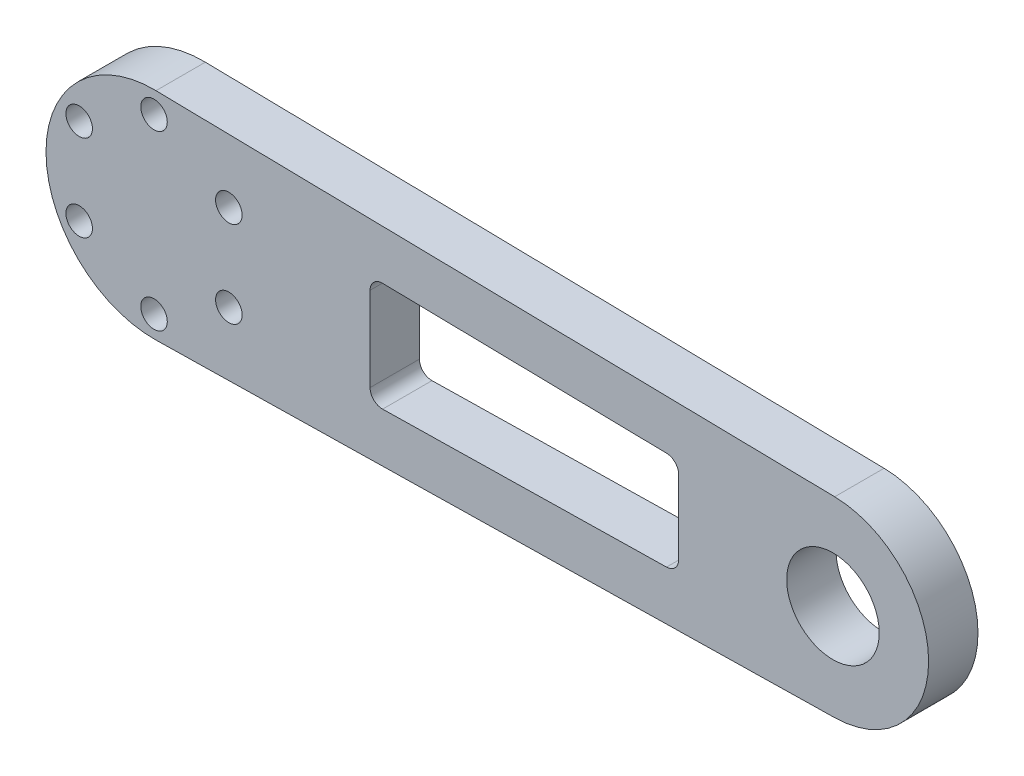
SolidWorks part; units mm, degrees
ref_plane "Front Plane" through (0, 0, 0) normal (0, 0, 1) x (1, 0, 0)
ref_plane "Top Plane" through (0, 0, 0) normal (0, 1, 0) x (1, 0, 0)
ref_plane "Right Plane" through (0, 0, 0) normal (1, 0, 0) x (0, 0, -1)
sketch "Sketch1" plane through (0, 0, 0) normal (0, 0, 1) x (1, 0, 0)
  line L0 (0, 0) -> (110, 0) construction
  line L1 (0.3182, 17.4971) -> (110.2818, 15.4974)
  line L2 (110, 0) -> (125.5, 0) construction
  line L3 (0.3182, -17.4971) -> (110.2818, -15.4974)
  line L4 (35, 6.8284) -> (35, -6.8284)
  line L5 (37.0364, 8.8281) -> (83.0364, 7.9916)
  line L6 (85, 5.9919) -> (85, -5.9919)
  line L7 (37.0364, -8.8281) -> (83.0364, -7.9916)
  circle A0 centre (0, 0) radius 17.5 construction
  circle A1 centre (0, 0) radius 14 construction
  circle A2 centre (0, 14) radius 2.1 construction
  circle A3 centre (12.1244, 7) radius 2.1 construction
  circle A4 centre (12.1244, -7) radius 2.1 construction
  circle A5 centre (0, -14) radius 2.1 construction
  circle A6 centre (-12.1244, -7) radius 2.1 construction
  circle A7 centre (-12.1244, 7) radius 2.1 construction
  arc A8 (110.2818, 15.4974) -> (110.2818, -15.4974) centre (110, 0) cw
  circle A9 centre (110, 0) radius 7.5
  arc A10 (83.0364, 7.9916) -> (85, 5.9919) centre (83, 5.9919) cw
  arc A11 (35, 6.8284) -> (37.0364, 8.8281) centre (37, 6.8284) cw
  arc A12 (35, -6.8284) -> (37.0364, -8.8281) centre (37, -6.8284) ccw
  arc A13 (83.0364, -7.9916) -> (85, -5.9919) centre (83, -5.9919) ccw
  arc A14 (0.3182, 17.4971) -> (0.3182, -17.4971) centre (0, 0) ccw
  point P18 (0, 0)
  point P26 (35, 0)
  point P38 (85, 0)
  point P39 (0, 0)
  dimension "D1" = 35
  dimension "D2" = 28
  dimension "D3" = 4.2
  dimension "D6" = 15
  dimension "D7" = 8
  dimension "D9" = 35
  dimension "D11" = 2
  dimension "D5" = 110
  dimension "D8" = 8
  dimension "D10" = 50
  dimension "D4" = 6
extrude "Boss-Extrude1" add sketch "Sketch1" along normal blind 8
hole_wizard "M4 Clearance Hole1" positions "Sketch2" profile "Sketch3" hole size "M4" standard "ISO"
sketch "Sketch2" plane through (0, 0, 8) normal (0, 0, 1) x (1, 0, 0)
  point P0 (12.1244, 7)
  point P3 (0, 14)
  point P6 (-12.1244, 7)
  point P9 (-12.1244, -7)
  point P12 (0, -14)
  point P15 (12.1244, -7)
sketch "Sketch3" plane through (12.1244, 7, 8) normal (1, 0, 0) x (0, -1, 0)
  line L0 (0, 0) -> (0, 26.2919)
  line L1 (0, 26.2919) -> (2.15, 25)
  line L2 (2.15, 25) -> (2.15, 0)
  line L5 (2.15, 0) -> (0, 0)
  line L10 (0, 26.2919) -> (-2.15, 25) construction
  line L11 (0, -6.35) -> (0, 107.95) construction
  dimension "Hole Dia." = 4.3
  dimension "Hole Depth" = 25
  dimension "Drill Angle" = 118
